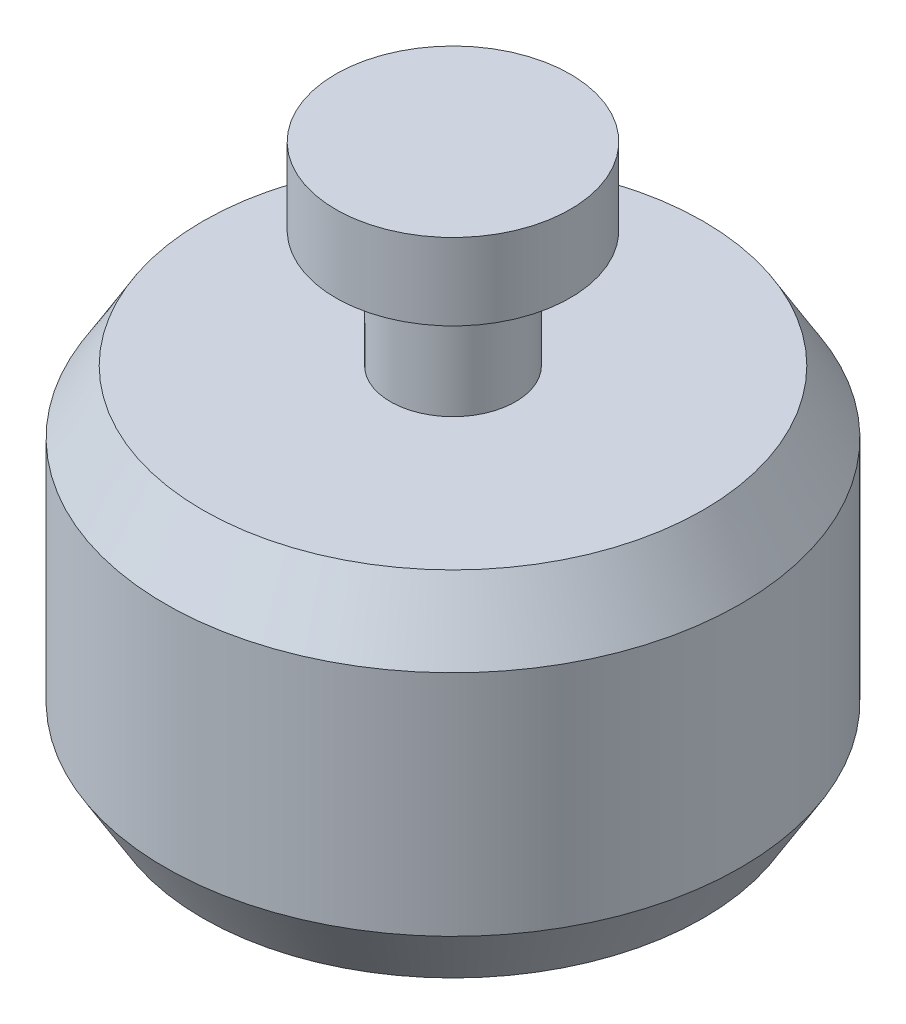
SolidWorks part; units mm, degrees
ref_plane "Front Plane" through (0, 0, 0) normal (0, 0, 1) x (1, 0, 0)
ref_plane "Top Plane" through (0, 0, 0) normal (0, 1, 0) x (1, 0, 0)
ref_plane "Right Plane" through (0, 0, 0) normal (1, 0, 0) x (0, 0, -1)
sketch "Sketch1" plane through (0, 0, 0) normal (0, 0, 1) x (1, 0, 0)
  line L0 (0, 0) -> (10.16, 0)
  line L1 (10.16, 0) -> (11.684, 2.54)
  line L2 (11.684, 2.54) -> (11.684, 11.811)
  line L3 (11.684, 11.811) -> (10.16, 14.351)
  line L4 (10.16, 14.351) -> (2.54, 14.351)
  line L5 (2.54, 14.351) -> (2.54, 19.1135)
  line L6 (2.54, 19.1135) -> (4.7625, 19.1135)
  line L7 (4.7625, 19.1135) -> (4.7625, 22.225)
  line L8 (4.7625, 22.225) -> (0, 22.225)
  line L9 (0, 22.225) -> (0, 0)
  dimension "D1" = 4.7625
  dimension "D2" = 11.684
  dimension "D3" = 14.351
  dimension "D4" = 2.54
  dimension "D5" = 10.16
  dimension "D6" = 2.54
  dimension "D7" = 22.225
  dimension "D8" = 4.7625
revolve "Revolve1" add sketch "Sketch1" angle 360 about L9
